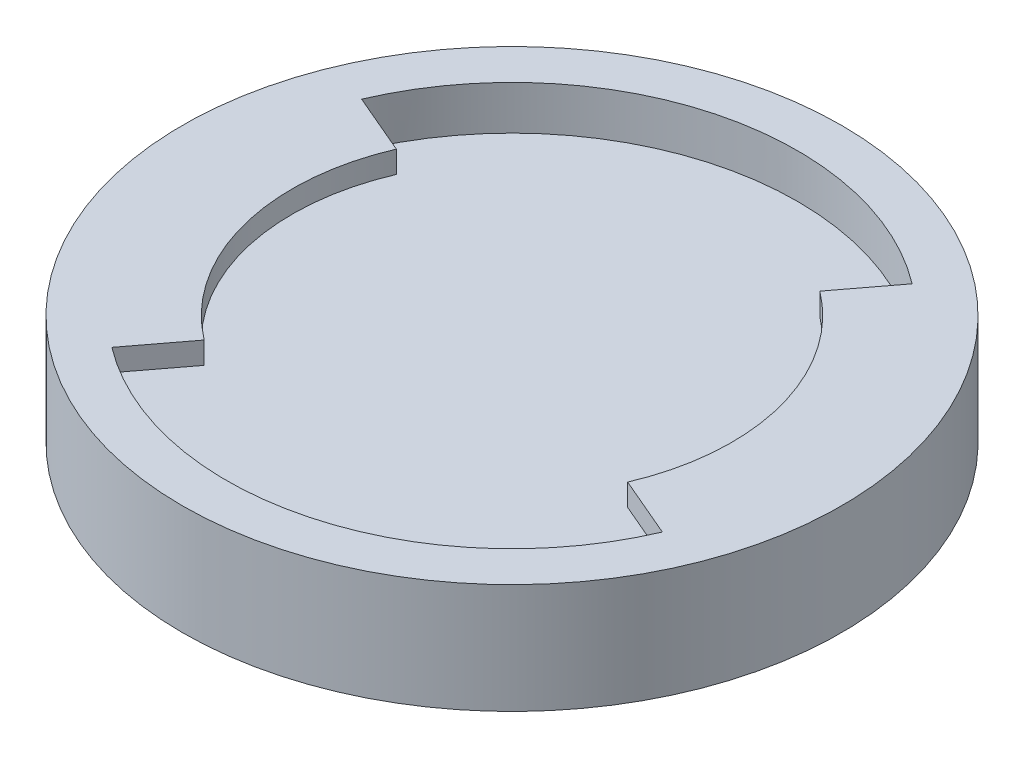
SolidWorks part; units mm, degrees
ref_plane "Ebene vorne" through (0, 0, 0) normal (0, 0, 1) x (1, 0, 0)
ref_plane "Ebene oben" through (0, 0, 0) normal (0, 1, 0) x (1, 0, 0)
ref_plane "Ebene rechts" through (0, 0, 0) normal (1, 0, 0) x (0, 0, -1)
sketch "Skizze1" plane through (0, 0, 0) normal (0, 1, 0) x (1, 0, 0)
  circle A0 centre (0, 0) radius 15
  dimension "D1" = 30
extrude "Aufsatz-Linear austragen1" add sketch "Skizze1" against normal blind 3
sketch "Skizze2" plane through (0, 0, 0) normal (0, 1, 0) x (1, 0, 0)
  circle A0 centre (0, 0) radius 15
  circle A1 centre (0, 0) radius 13
  dimension "D1" = 26
extrude "Aufsatz-Linear austragen2" add sketch "Skizze2" along normal blind 2
sketch "Skizze3" plane through (0, 2, 0) normal (0, 1, 0) x (1, 0, 0)
  line L0 (0, 0) -> (21.5569, -9.2148) construction
  line L1 (0, 0) -> (-22.5777, 9.6512) construction
  line L2 (0, 0) -> (14.6044, 19.2602) construction
  line L3 (0, 0) -> (-17.7821, -23.451) construction
  line L4 (-6.0421, -7.9683) -> (-7.8547, -10.3587)
  line L5 (-9.1951, 3.9306) -> (-11.9537, 5.1098)
  line L6 (6.0421, 7.9683) -> (7.8547, 10.3587)
  line L7 (9.1951, -3.9306) -> (11.9537, -5.1098)
  arc A0 (7.8547, 10.3587) -> (11.9537, -5.1098) centre (0, 0) cw
  circle A1 centre (0, 0) radius 13 construction
  arc A2 (6.0421, 7.9683) -> (9.1951, -3.9306) centre (0, 0) cw
  arc A3 (-11.9537, 5.1098) -> (-7.8547, -10.3587) centre (0, 0) ccw
  arc A4 (-9.1951, 3.9306) -> (-6.0421, -7.9683) centre (0, 0) ccw
extrude "Aufsatz-Linear austragen3" add sketch "Skizze3" against normal blind 1
